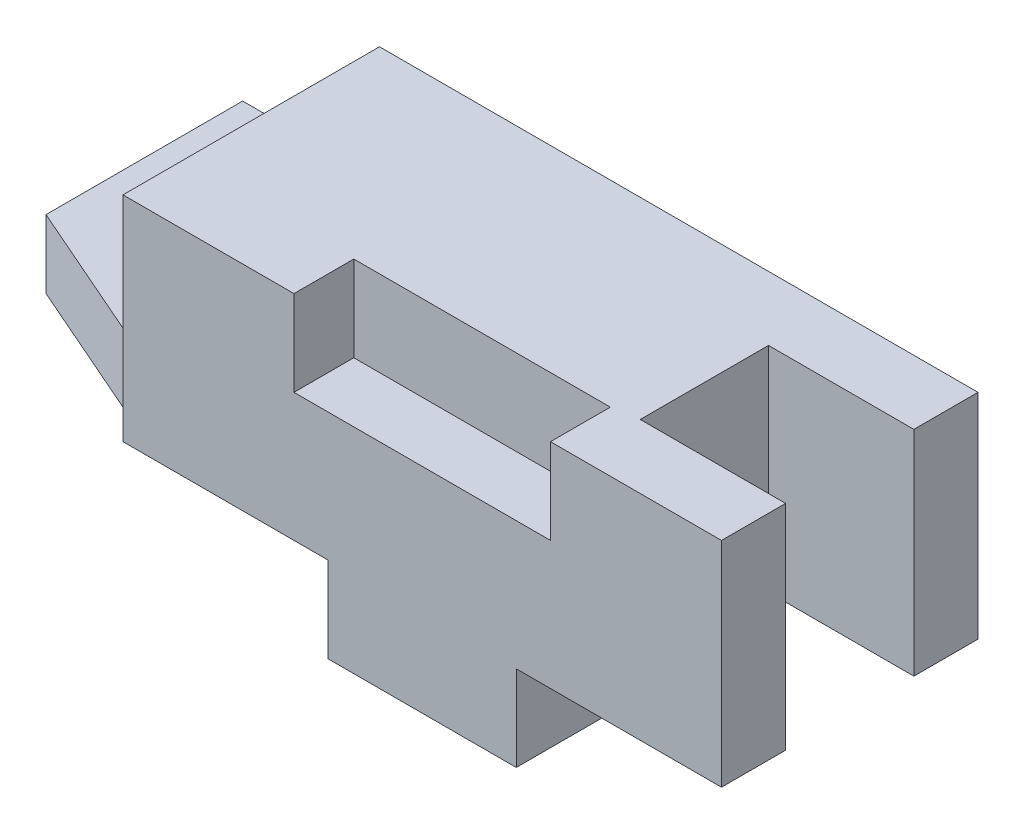
SolidWorks part; units mm, degrees
ref_plane "Спереди" through (0, 0, 0) normal (0, 0, 1) x (1, 0, 0)
ref_plane "Сверху" through (0, 0, 0) normal (0, 1, 0) x (1, 0, 0)
ref_plane "Справа" through (0, 0, 0) normal (1, 0, 0) x (0, 0, -1)
sketch "Эскиз1" plane through (0, 0, 0) normal (0, 0, 1) x (1, 0, 0)
  line L0 (-11, -7.5) -> (-35, -7.5)
  line L1 (-35, -17.5) -> (35, -17.5)
  line L2 (-35, -17.5) -> (-35, 17.5)
  line L3 (-35, 17.5) -> (35, 17.5)
  line L4 (35, -17.5) -> (35, 17.5)
  line L5 (-35, -17.5) -> (35, 17.5) construction
  line L6 (-35, 17.5) -> (35, -17.5) construction
  line L7 (-11, -7.5) -> (11, -7.5)
  line L8 (-11, -7.5) -> (-11, -17.5)
  line L9 (-11, -17.5) -> (11, -17.5)
  line L10 (11, -7.5) -> (11, -17.5)
  line L11 (-11, -7.5) -> (11, -17.5) construction
  line L12 (-11, -17.5) -> (11, -7.5) construction
  line L13 (11, -7.5) -> (35, -7.5)
  line L15 (-51, -4) -> (-35, -4)
  line L16 (-51, -4) -> (-51, 4)
  line L17 (-51, 4) -> (-35, 4)
  line L18 (-35, -4) -> (-35, 4)
  line L19 (-51, -4) -> (-35, 4) construction
  line L20 (-51, 4) -> (-35, -4) construction
  point P0 (0, 0)
  point P6 (0, -12.5)
  point P13 (-43, 0)
  dimension "D1" = 35
  dimension "D2" = 70
  dimension "D3" = 22
  dimension "D4" = 10
  dimension "D5" = 8
  dimension "D6" = 16
extrude "Бобышка-Вытянуть1" add sketch "Эскиз1" along normal blind 30 contours L7 L13 L4 L3 L2 L0 | L10 L7 L8 L1 | L17 L16 L15 L2
sketch "Эскиз2" plane through (0, -4, 0) normal (0, -1, 0) x (1, 0, 0)
  line L0 (-51, 30) -> (-35, 30)
  line L1 (-35, 30) -> (-51, 23)
  line L2 (-51, 30) -> (-51, 0) construction
  line L3 (-51, 23) -> (-51, 30)
  line L4 (35, 15) -> (-51, 15) construction
  line L5 (35, 30) -> (35, 0) construction
  line L7 (18, 7.5) -> (35, 7.5)
  line L8 (18, 7.5) -> (18, 22.5)
  line L9 (18, 22.5) -> (35, 22.5)
  line L10 (35, 7.5) -> (35, 22.5)
  line L11 (18, 7.5) -> (35, 22.5) construction
  line L12 (18, 22.5) -> (35, 7.5) construction
  point P11 (26.5, 15)
  line M6 (-35, 30) -> (-51, 30)
  line M7 (-51, 30) -> (-51, 0)
  dimension "D1" = 7
  dimension "D2" = 15
  dimension "D3" = 17
extrude "Вырез-Вытянуть1" cut sketch "Эскиз2" against normal blind 30 and the other way blind 30 contours L7 L10 L9 L8 | L1 M6 M7
sketch "Эскиз3" plane through (0, 0, 30) normal (0, 0, 1) x (1, 0, 0)
  line L0 (-35, 17.5) -> (35, 17.5) construction
  line L1 (-15, 7.5) -> (15, 7.5)
  line L2 (-15, 7.5) -> (-15, 17.5)
  line L3 (-15, 17.5) -> (15, 17.5)
  line L4 (15, 7.5) -> (15, 17.5)
  line L5 (-15, 7.5) -> (15, 17.5) construction
  line L6 (-15, 17.5) -> (15, 7.5) construction
  point P0 (0, 12.5)
  dimension "D1" = 30
  dimension "D2" = 10
extrude "Вырез-Вытянуть2" cut sketch "Эскиз3" against normal blind 7
